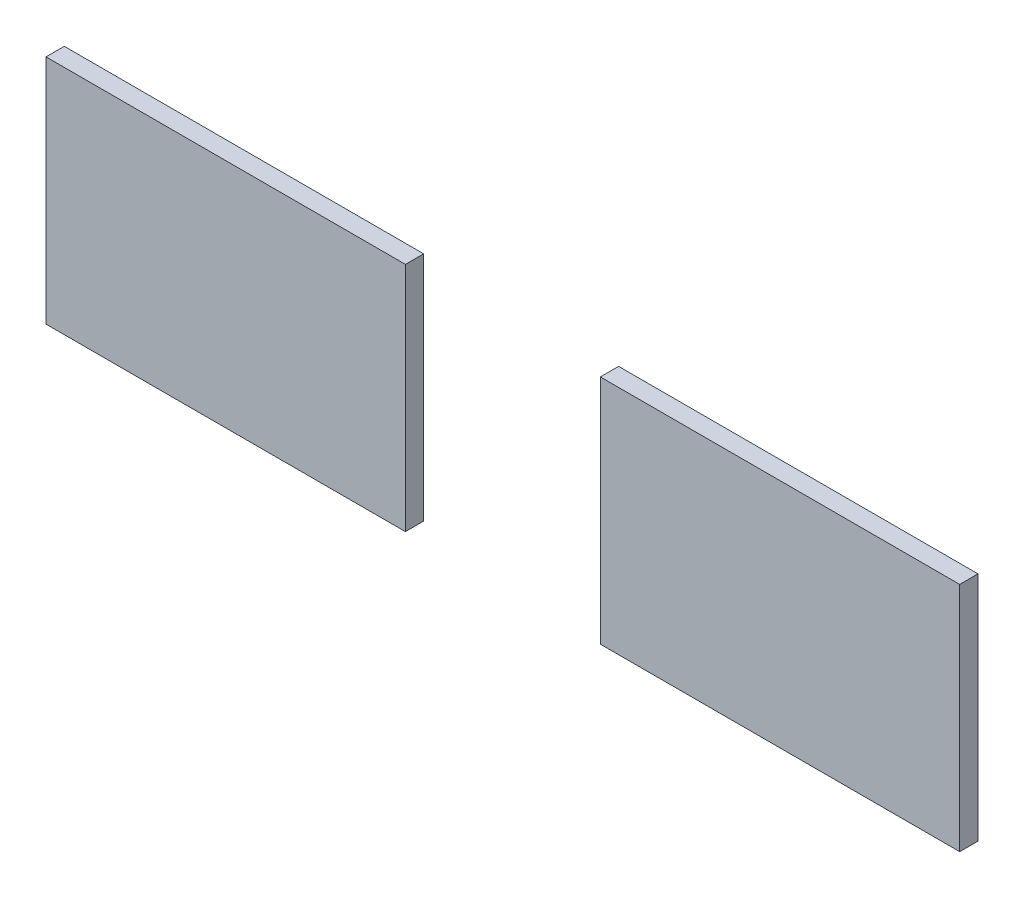
SolidWorks part; units mm, degrees
ref_plane "Front Plane" through (0, 0, 0) normal (0, 0, 1) x (1, 0, 0)
ref_plane "Top Plane" through (0, 0, 0) normal (0, 1, 0) x (1, 0, 0)
ref_plane "Right Plane" through (0, 0, 0) normal (1, 0, 0) x (0, 0, -1)
sketch "Sketch1" plane through (0, 0, 0) normal (0, 0, 1) x (1, 0, 0)
  line L1 (-64.3636, 9.1667) -> (-34.8636, 9.1667)
  line L2 (-64.3636, 9.1667) -> (-64.3636, -9.8333)
  line L3 (-64.3636, -9.8333) -> (-34.8636, -9.8333)
  line L4 (-34.8636, 9.1667) -> (-34.8636, -9.8333)
  line L5 (-18.8636, 9.1667) -> (10.6364, 9.1667)
  line L6 (-18.8636, 9.1667) -> (-18.8636, -9.8333)
  line L7 (-18.8636, -9.8333) -> (10.6364, -9.8333)
  line L8 (10.6364, 9.1667) -> (10.6364, -9.8333)
  dimension "D1" = 29.5
  dimension "D2" = 19
  dimension "D3" = 29.5
  dimension "D4" = 16
  dimension "D5" = 19
extrude "Boss-Extrude1" add sketch "Sketch1" along normal blind 1.5
